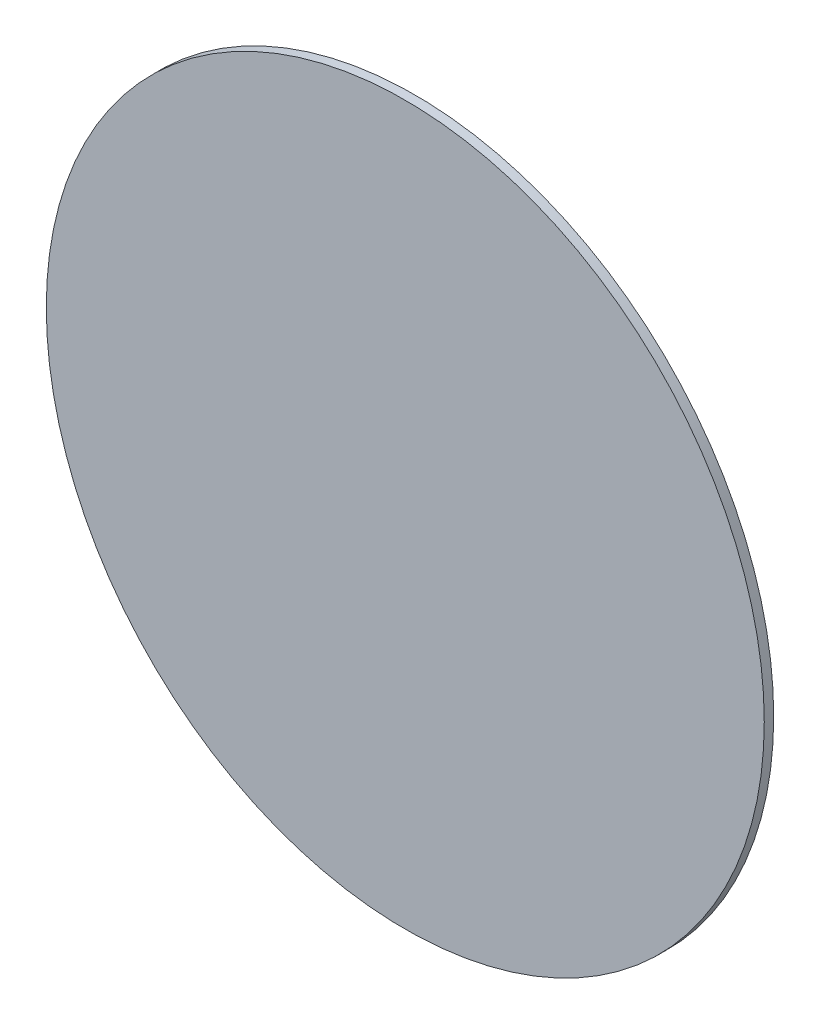
SolidWorks part; units mm, degrees
ref_plane "Plan de face" through (0, 0, 0) normal (0, 0, 1) x (1, 0, 0)
ref_plane "Plan de dessus" through (0, 0, 0) normal (0, 1, 0) x (1, 0, 0)
ref_plane "Plan de droite" through (0, 0, 0) normal (1, 0, 0) x (0, 0, -1)
sketch "Esquisse1" plane through (0, 0, 0) normal (0, 0, 1) x (1, 0, 0)
  circle A0 centre (0, 0) radius 190
  dimension "D1" = 380
extrude "Boss.-Extru.1" add sketch "Esquisse1" along normal blind 5
